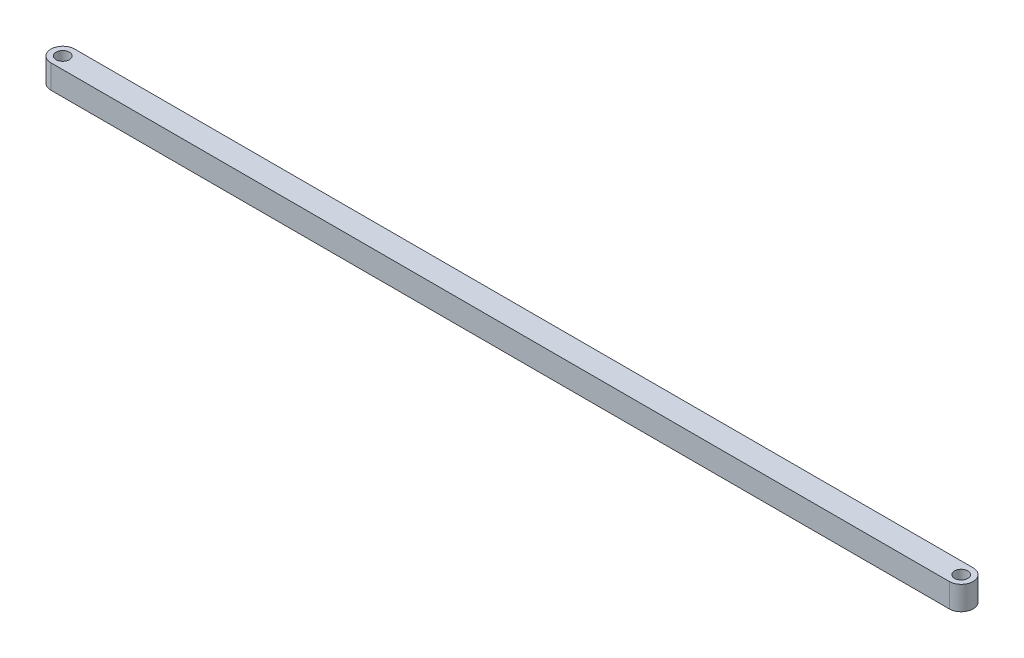
SolidWorks part; units mm, degrees
ref_plane "Front Plane" through (0, 0, 0) normal (0, 0, 1) x (1, 0, 0)
ref_plane "Top Plane" through (0, 0, 0) normal (0, 1, 0) x (1, 0, 0)
ref_plane "Right Plane" through (0, 0, 0) normal (1, 0, 0) x (0, 0, -1)
ref_plane "Plane1" through (0, 4.5, 0) normal (0, 1, 0) x (1, 0, 0)
sketch "Sketch1" plane through (0, 4.5, 0) normal (0, 1, 0) x (1, 0, 0)
  line L0 (170, 4.5) -> (-170, 4.5)
  line L1 (-170, -4.5) -> (170, -4.5)
  circle A0 centre (170, 0) radius 2.5
  arc A1 (-170, 4.5) -> (-170, -4.5) centre (-170, 0) ccw
  arc A2 (170, -4.5) -> (170, 4.5) centre (170, 0) ccw
  circle A3 centre (-170, 0) radius 2.5
extrude "Boss-Extrude1" add sketch "Sketch1" against normal blind 9
